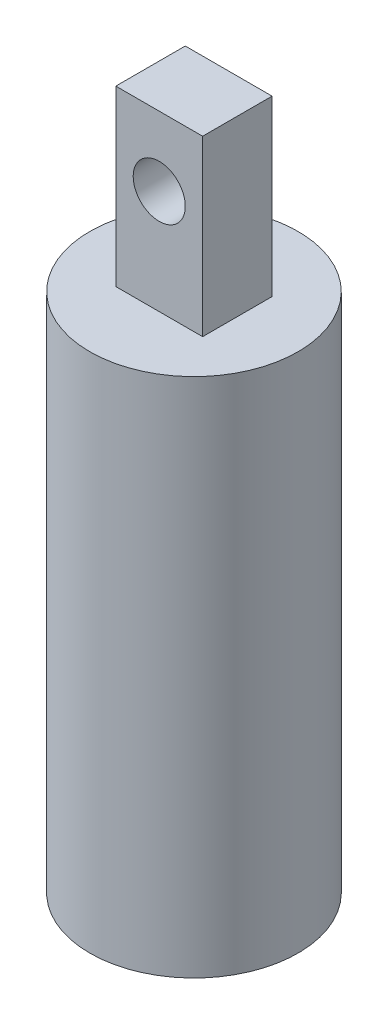
SolidWorks part; units mm, degrees
ref_plane "Front Plane" through (0, 0, 0) normal (0, 0, 1) x (1, 0, 0)
ref_plane "Top Plane" through (0, 0, 0) normal (0, 1, 0) x (1, 0, 0)
ref_plane "Right Plane" through (0, 0, 0) normal (1, 0, 0) x (0, 0, -1)
sketch "Sketch2" plane through (0, 0, 0) normal (0, 1, 0) x (1, 0, 0)
  circle A0 centre (0, 0) radius 30
  dimension "D1" = 60
extrude "Boss-Extrude1" add sketch "Sketch2" along normal blind 150
sketch "Sketch3" plane through (0, 0, 0) normal (1, 0, 0) x (0, 0, -1)
  line L0 (0, 0) -> (0, 50)
  circle A0 centre (0, 50) radius 20
  dimension "D2" = 40
  dimension "D1" = 50
extrude "Cut-Extrude1" cut sketch "Sketch3" against normal blind 100
sketch "Sketch4" plane through (0, 150, 0) normal (0, 1, 0) x (1, 0, 0)
  line L1 (-12.5, -10) -> (12.5, -10)
  line L2 (-12.5, -10) -> (-12.5, 10)
  line L3 (-12.5, 10) -> (12.5, 10)
  line L4 (12.5, -10) -> (12.5, 10)
  line L5 (-12.5, -10) -> (12.5, 10) construction
  line L6 (-12.5, 10) -> (12.5, -10) construction
  point P0 (0, 0)
  dimension "D1" = 20
  dimension "D2" = 25
extrude "Boss-Extrude2" add sketch "Sketch4" along normal blind 50
sketch "Sketch5" plane through (0, 0, -10) normal (0, 0, -1) x (-1, 0, 0)
  line L0 (-12.5, 200) -> (12.5, 200) construction
  circle A0 centre (0, 180) radius 7.5
  dimension "D2" = 15
  dimension "D1" = 20
extrude "Cut-Extrude2" cut sketch "Sketch5" against normal blind 40
